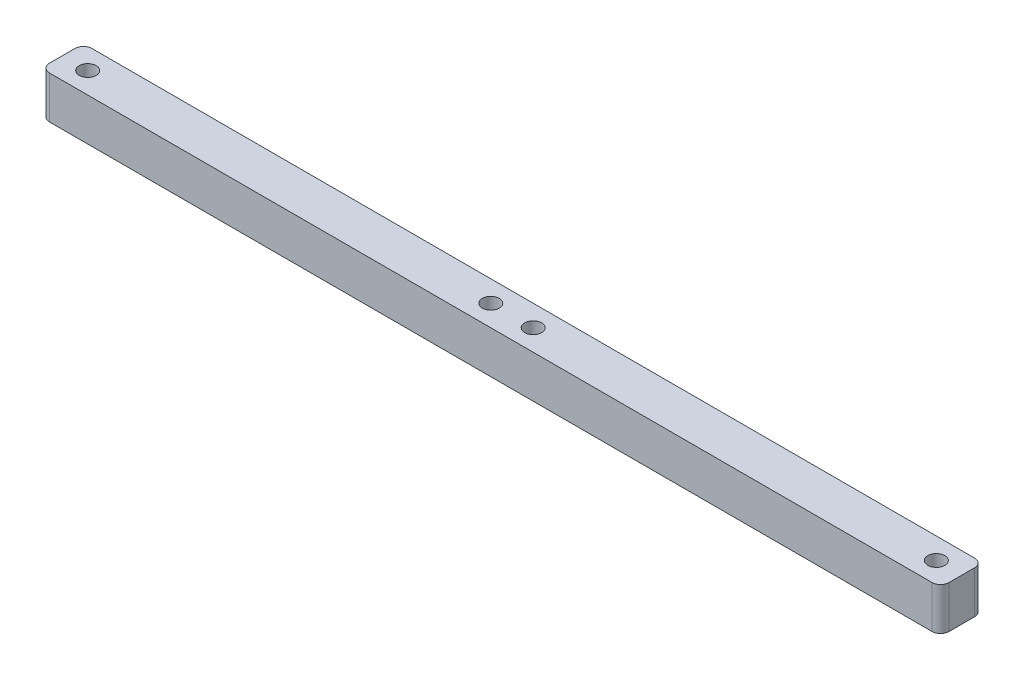
SolidWorks part; units mm, degrees
ref_plane "Front Plane" through (0, 0, 0) normal (0, 0, 1) x (1, 0, 0)
ref_plane "Top Plane" through (0, 0, 0) normal (0, 1, 0) x (1, 0, 0)
ref_plane "Right Plane" through (0, 0, 0) normal (1, 0, 0) x (0, 0, -1)
sketch "Sketch1" plane through (0, 0, 0) normal (0, 1, 0) x (1, 0, 0)
  line L1 (-53, 2.5) -> (53, 2.5)
  line L2 (-53, 2.5) -> (-53, -2.5)
  line L3 (-53, -2.5) -> (53, -2.5)
  line L4 (53, 2.5) -> (53, -2.5)
  line L5 (-53, 2.5) -> (53, -2.5) construction
  line L6 (-53, -2.5) -> (53, 2.5) construction
  point P0 (0, 0)
  dimension "D1" = 106
  dimension "D2" = 5
extrude "Boss-Extrude1" add sketch "Sketch1" along normal blind 5
fillet "Fillet1" radius 1 2 edges at (-53, 2.5, -2.5) (-53, 2.5, 2.5)
fillet "Fillet2" radius 1 2 edges at (53, 2.5, -2.5) (53, 2.5, 2.5)
sketch "Sketch2" plane through (0, 5, 0) normal (0, 1, 0) x (1, 0, 0)
  line L0 (-53, 1.5) -> (-53, -1.5) construction
  line L1 (-52, -2.5) -> (52, -2.5) construction
  line L2 (53, -1.5) -> (53, 1.5) construction
  line L3 (52, 2.5) -> (-52, 2.5) construction
  line L4 (-2.5, 0) -> (2.5, 0) construction
  circle A0 centre (-50, 0) radius 1
  circle A1 centre (50, 0) radius 1
  circle A3 centre (-2.5, 0) radius 1
  circle A4 centre (2.5, 0) radius 1
  point P17 (0, 0)
  dimension "D1" = 2
  dimension "D6" = 2
  dimension "D7" = 5
  dimension "D8" = 2
  dimension "D9" = 2
  dimension "D2" = 3
  dimension "D3" = 2.5
  dimension "D4" = 3
  dimension "D5" = 2.5
extrude "Cut-Extrude1" cut sketch "Sketch2" against normal through all
